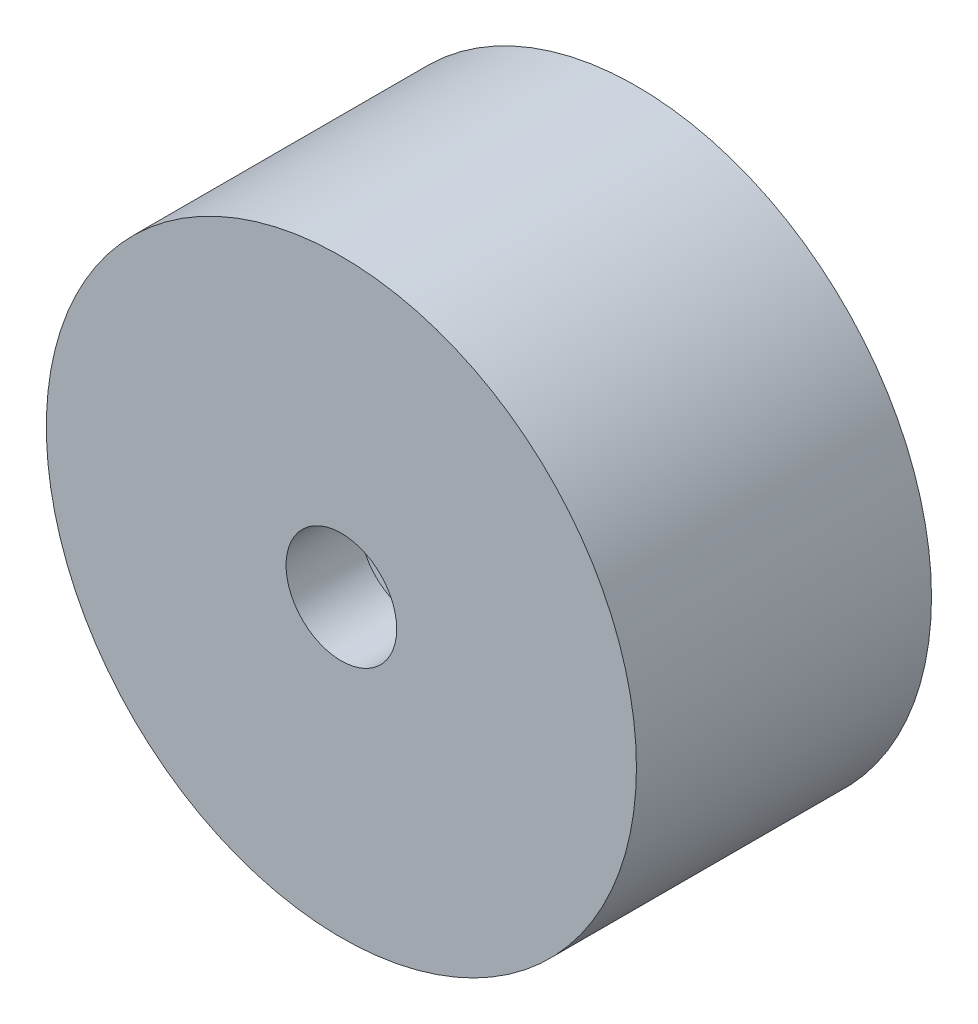
SolidWorks part; units mm, degrees
ref_plane "前视基准面" through (0, 0, 0) normal (0, 0, 1) x (1, 0, 0)
ref_plane "上视基准面" through (0, 0, 0) normal (0, 1, 0) x (1, 0, 0)
ref_plane "右视基准面" through (0, 0, 0) normal (1, 0, 0) x (0, 0, -1)
sketch "草图1" plane through (0, 0, 0) normal (0, 0, 1) x (1, 0, 0)
  circle A1 centre (0, 0) radius 8
  dimension "D1" = 16
extrude "凸台-拉伸1" add sketch "草图1" along normal blind 8
sketch "草图2" plane through (0, 0, 0) normal (0, 0, -1) x (-1, 0, 0)
  circle A0 centre (0, 0) radius 6
  dimension "D1" = 12
extrude "切除-拉伸1" cut sketch "草图2" against normal blind 6
sketch "草图3" plane through (0, 0, 8) normal (0, 0, 1) x (1, 0, 0)
  circle A0 centre (0, 0) radius 1.5
  dimension "D1" = 3
extrude "切除-拉伸2" cut sketch "草图3" against normal through all
